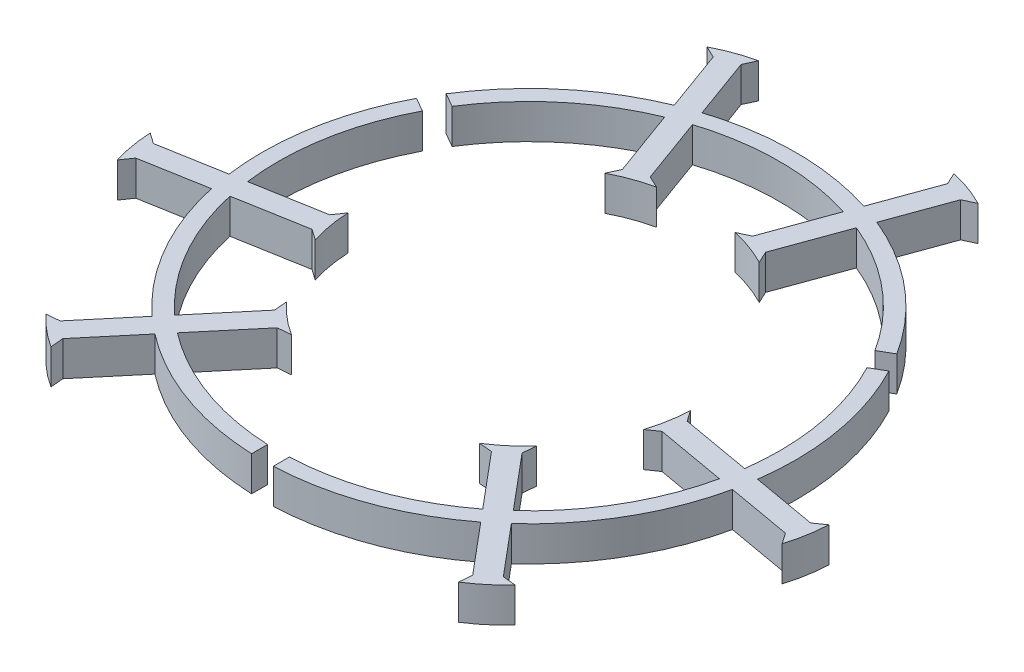
SolidWorks part; units mm, degrees
ref_plane "Front Plane" through (0, 0, 0) normal (0, 0, 1) x (1, 0, 0)
ref_plane "Top Plane" through (0, 0, 0) normal (0, 1, 0) x (1, 0, 0)
ref_plane "Right Plane" through (0, 0, 0) normal (1, 0, 0) x (0, 0, -1)
sketch "Sketch1" plane through (0, 0, 0) normal (0, 1, 0) x (1, 0, 0)
  line L0 (0, 0) -> (0, -32.16) construction
  line L1 (-20.4965, 11.8337) -> (-21.0065, 10.9503) construction
  line L2 (0, 0) -> (-27.8514, 16.08) construction
  line L3 (0, 0) -> (27.8514, 16.08) construction
  line L4 (-20.4965, 11.8337) -> (-19.9865, 12.717) construction
  line L13 (-6.724, 15.4919) -> (-7.2439, 14.377)
  line L14 (-8.9987, 21.7413) -> (-6.724, 15.4919)
  line L15 (-9.5113, 23.1498) -> (-11.6081, 28.9107)
  line L16 (-11.6081, 28.9107) -> (-12.723, 29.4306)
  line L17 (-9.6911, 29.6084) -> (-9.1712, 30.7233)
  line L18 (-7.5943, 23.8475) -> (-9.6911, 29.6084)
  line L19 (-7.0817, 22.439) -> (-4.8071, 16.1896)
  line L20 (-4.8071, 16.1896) -> (-3.6922, 15.6697)
  line L21 (4.8071, 16.1896) -> (3.6922, 15.6697)
  line L22 (7.0817, 22.439) -> (4.8071, 16.1896)
  line L23 (7.5943, 23.8475) -> (9.6911, 29.6084)
  line L24 (9.6911, 29.6084) -> (9.1712, 30.7233)
  line L25 (11.6081, 28.9107) -> (12.723, 29.4306)
  line L26 (9.5113, 23.1498) -> (11.6081, 28.9107)
  line L27 (8.9987, 21.7413) -> (6.724, 15.4919)
  line L28 (6.724, 15.4919) -> (7.2439, 14.377)
  line L37 (16.7784, -1.9227) -> (16.0728, -0.9151)
  line L38 (23.3279, -3.0776) -> (16.7784, -1.9227)
  line L39 (24.8039, -3.3379) -> (30.8414, -4.4024)
  line L40 (30.8414, -4.4024) -> (31.8491, -3.6969)
  line L41 (30.4872, -6.4115) -> (31.1928, -7.4191)
  line L42 (24.4497, -5.3469) -> (30.4872, -6.4115)
  line L43 (22.9736, -5.0866) -> (16.4241, -3.9318)
  line L44 (16.4241, -3.9318) -> (15.4165, -4.6373)
  line L45 (11.6171, -12.2579) -> (11.7243, -11.0324)
  line L46 (15.8919, -17.3524) -> (11.6171, -12.2579)
  line L47 (16.8554, -18.5006) -> (20.7961, -23.197)
  line L48 (20.7961, -23.197) -> (22.0215, -23.3042)
  line L49 (19.2333, -24.5083) -> (19.1261, -25.7337)
  line L50 (15.2926, -19.8119) -> (19.2333, -24.5083)
  line L51 (14.3292, -18.6637) -> (10.0543, -13.5691)
  line L52 (10.0543, -13.5691) -> (8.8289, -13.4619)
  line L61 (-10.0543, -13.5691) -> (-8.8289, -13.4619)
  line L62 (-14.3292, -18.6637) -> (-10.0543, -13.5691)
  line L63 (-15.2926, -19.8119) -> (-19.2333, -24.5083)
  line L64 (-19.2333, -24.5083) -> (-19.1261, -25.7337)
  line L65 (-20.7961, -23.197) -> (-22.0215, -23.3042)
  line L66 (-16.8554, -18.5006) -> (-20.7961, -23.197)
  line L67 (-15.8919, -17.3524) -> (-11.6171, -12.2579)
  line L68 (-11.6171, -12.2579) -> (-11.7243, -11.0324)
  line L69 (-16.4241, -3.9318) -> (-15.4165, -4.6373)
  line L70 (-22.9736, -5.0866) -> (-16.4241, -3.9318)
  line L71 (-24.4497, -5.3469) -> (-30.4872, -6.4115)
  line L72 (-30.4872, -6.4115) -> (-31.1928, -7.4191)
  line L73 (-30.8414, -4.4024) -> (-31.8491, -3.6969)
  line L74 (-24.8039, -3.3379) -> (-30.8414, -4.4024)
  line L75 (-23.3279, -3.0776) -> (-16.7784, -1.9227)
  line L76 (-16.7784, -1.9227) -> (-16.0728, -0.9151)
  line L77 (20.4965, 11.8337) -> (21.0065, 10.9503) construction
  line L78 (20.4965, 11.8337) -> (19.9865, 12.717) construction
  line L79 (0, -23.6674) -> (-1.02, -23.6674) construction
  line L80 (0, -23.6674) -> (1.02, -23.6674) construction
  line L81 (-1.02, -23.6674) -> (-1.02, -19.4862) construction
  line L82 (-1.02, -23.6674) -> (-1.02, -27.6221) construction
  line L83 (1.02, -23.6674) -> (1.02, -27.6221) construction
  line L84 (1.02, -23.6674) -> (1.02, -19.4862) construction
  line L85 (-21.0065, 10.9503) -> (-17.3855, 8.8597) construction
  line L86 (-21.0065, 10.9503) -> (-24.4315, 12.9277) construction
  line L87 (-19.9865, 12.717) -> (-23.4115, 14.6944) construction
  line L88 (-19.9865, 12.717) -> (-16.3655, 10.6264) construction
  line L89 (19.9865, 12.717) -> (16.3655, 10.6264) construction
  line L90 (19.9865, 12.717) -> (23.4115, 14.6944) construction
  line L91 (21.0065, 10.9503) -> (24.4315, 12.9277) construction
  line L92 (21.0065, 10.9503) -> (17.3855, 8.8597) construction
  line L93 (-1.02, -23.5079) -> (-1.02, -25.0067)
  line L94 (1.02, -23.5079) -> (1.02, -25.0067)
  line L95 (-21.1464, 13.3867) -> (-19.8484, 12.6373)
  line L96 (-22.1664, 11.62) -> (-20.8684, 10.8706)
  line L97 (20.8684, 10.8706) -> (22.1664, 11.62)
  line L98 (19.8484, 12.6373) -> (21.1464, 13.3867)
  circle A0 centre (0, 0) radius 15.895 construction
  circle A1 centre (0, 0) radius 32.16 construction
  arc A4 (-3.6922, 15.6697) -> (-7.2439, 14.377) centre (-0.5244, 1.4408) ccw
  arc A5 (-12.723, 29.4306) -> (-9.1712, 30.7233) centre (-5.9797, 16.4292) cw
  arc A6 (7.2439, 14.377) -> (3.6922, 15.6697) centre (0.5244, 1.4408) ccw
  arc A7 (9.1712, 30.7233) -> (12.723, 29.4306) centre (5.9797, 16.4292) cw
  arc A10 (15.4165, -4.6373) -> (16.0728, -0.9151) centre (1.51, -0.2662) ccw
  arc A11 (31.8491, -3.6969) -> (31.1928, -7.4191) centre (17.2179, -3.036) cw
  arc A12 (8.8289, -13.4619) -> (11.7243, -11.0324) centre (0.9856, -1.1745) ccw
  arc A13 (22.0215, -23.3042) -> (19.1261, -25.7337) centre (11.2382, -13.3932) cw
  arc A16 (-11.7243, -11.0324) -> (-8.8289, -13.4619) centre (-0.9856, -1.1745) ccw
  arc A17 (-19.1261, -25.7337) -> (-22.0215, -23.3042) centre (-11.2382, -13.3932) cw
  arc A18 (-16.0728, -0.9151) -> (-15.4165, -4.6373) centre (-1.51, -0.2662) ccw
  arc A19 (-31.1928, -7.4191) -> (-31.8491, -3.6969) centre (-17.2179, -3.036) cw
  arc A20 (1.02, -23.5079) -> (14.3292, -18.6637) centre (0, 0) ccw
  arc A21 (1.02, -25.0067) -> (15.2926, -19.8119) centre (0, 0) ccw
  arc A22 (-20.8684, 10.8706) -> (-23.3279, -3.0776) centre (0, 0) ccw
  arc A23 (-22.1664, 11.62) -> (-24.8039, -3.3379) centre (0, 0) ccw
  arc A24 (21.1464, 13.3867) -> (9.5113, 23.1498) centre (0, 0) ccw
  arc A25 (19.8484, 12.6373) -> (8.9987, 21.7413) centre (0, 0) ccw
  arc A26 (-8.9987, 21.7413) -> (-19.8484, 12.6373) centre (0, 0) ccw
  arc A27 (-9.5113, 23.1498) -> (-21.1464, 13.3867) centre (0, 0) ccw
  arc A28 (7.5943, 23.8475) -> (-7.5943, 23.8475) centre (0, 0) ccw
  arc A29 (7.0817, 22.439) -> (-7.0817, 22.439) centre (0, 0) ccw
  arc A30 (24.8039, -3.3379) -> (22.1664, 11.62) centre (0, 0) ccw
  arc A31 (23.3279, -3.0776) -> (20.8684, 10.8706) centre (0, 0) ccw
  arc A32 (15.8919, -17.3524) -> (22.9736, -5.0866) centre (0, 0) ccw
  arc A33 (16.8554, -18.5006) -> (24.4497, -5.3469) centre (0, 0) ccw
  arc A34 (-14.3292, -18.6637) -> (-1.02, -23.5079) centre (0, 0) ccw
  arc A35 (-15.2926, -19.8119) -> (-1.02, -25.0067) centre (0, 0) ccw
  arc A36 (-24.4497, -5.3469) -> (-16.8554, -18.5006) centre (0, 0) ccw
  arc A37 (-22.9736, -5.0866) -> (-15.8919, -17.3524) centre (0, 0) ccw
  point P19 (0, 0)
  point P87 (0, 0)
  point P119 (0, 0)
  dimension "D1" = 31.79
  dimension "D2" = 64.32
  dimension "D4" = 50.055
  dimension "D5" = 47.06
  dimension "D3" = 3
  dimension "D6" = 3
extrude "Boss-Extrude1" add sketch "Sketch1" along normal blind 3.265
